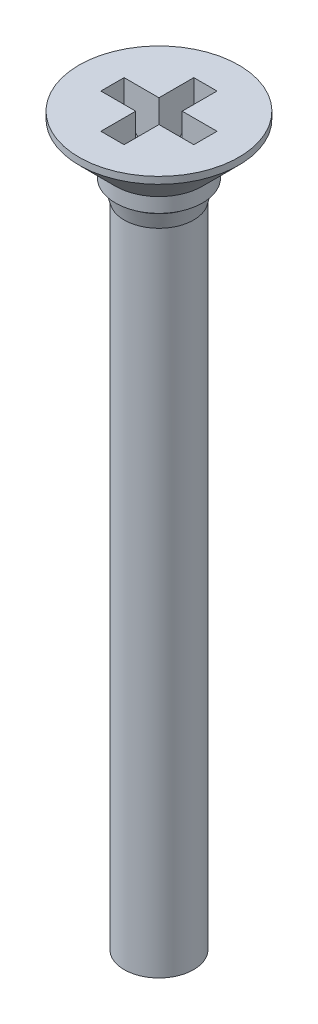
SolidWorks part; units mm, degrees
ref_plane "Vorderseite" through (0, 0, 0) normal (0, 0, 1) x (1, 0, 0)
ref_plane "Oben" through (0, 0, 0) normal (0, 1, 0) x (1, 0, 0)
ref_plane "Rechts" through (0, 0, 0) normal (1, 0, 0) x (0, 0, -1)
sketch "Skizze1" plane through (0, 0, 0) normal (0, 0, 1) x (1, 0, 0)
  line L0 (0, 0) -> (2.75, 0)
  line L1 (2.75, 0) -> (2.75, -0.2375)
  line L2 (2.75, -0.2375) -> (1.5, -1.4875)
  line L3 (1.3375, -1.9875) -> (1.3375, -2.1126)
  line L4 (1.3375, -2.1126) -> (1.1935, -2.65)
  line L5 (1.1935, -2.65) -> (1.1935, -8)
  line L6 (1.1935, -8) -> (0, -8)
  line L7 (0, 0) -> (0, -8) construction
  line L8 (0, 0) -> (0, -8)
  line L10 (1.5, -1.4875) -> (1.5, -1.9875)
  line L12 (1.5, -1.9875) -> (1.3375, -1.9875)
  point P3 (1.3375, -1.65)
  dimension "D1" = 45
  dimension "D2" = 15
  dimension "K" = 1.65
  dimension "DA" = 5.5
  dimension "DK" = 2.387
  dimension "L" = 8
  dimension "DG" = 3
  dimension "A" = 1
  dimension "DF" = 2.675
  dimension "P" = 0.5
revolve "Basis-Rotation" add sketch "Skizze1" angle 360 about L7
sketch "Skizze2" plane through (0, 0, 0) normal (0, 0, 1) x (1, 0, 0)
  line L0 (0, -2.1) -> (0, 0) construction
  line L1 (0, 0) -> (0, -8) construction
  line L2 (-0.55, -2.1) -> (0.55, -2.1)
  line L3 (1.6, 0) -> (1.6, -1.05)
  line L4 (1.6, -1.05) -> (0.55, -2.1)
  line L5 (1.6, 0) -> (-1.6, 0)
  line L6 (-1.6, -1.05) -> (-0.55, -2.1)
  line L7 (-1.6, 0) -> (-1.6, -1.05)
  line L8 (0, -1.05) -> (1.6, -1.05) construction
  line L9 (2.75, 0) -> (-2.75, 0) construction
  line L11 (1.5, -1.4875) -> (2.75, -0.2375) construction
  point P11 (0, 0)
  dimension "M" = 3.2
  dimension "T" = 2.1
extrude "Kreuzschlitz1 H" cut sketch "Skizze2" against normal blind 0.4 and the other way blind 0.4
sketch "Skizze3" plane through (0, 0, 0) normal (1, 0, 0) x (0, 0, -1)
  line L0 (0, -2.1) -> (0, 0) construction
  line L2 (-0.55, -2.1) -> (0.55, -2.1)
  line L3 (1.6, 0) -> (1.6, -1.05)
  line L4 (1.6, -1.05) -> (0.55, -2.1)
  line L5 (1.6, 0) -> (-1.6, 0)
  line L6 (-1.6, -1.05) -> (-0.55, -2.1)
  line L7 (-1.6, 0) -> (-1.6, -1.05)
  line L8 (0, -1.05) -> (1.6, -1.05) construction
  point P11 (0, 0)
extrude "Kreuzschlitz2 H" cut sketch "Skizze3" against normal blind 0.4 and the other way blind 0.4
sketch "Skizze4" plane through (2.4522, 0, -1.8507) normal (0, 1, 0) x (-1, 0, 0)
  line L0 (7.3522, 1.8507) -> (-2.4478, 1.8507) construction
  line L1 (2.4522, -3.0493) -> (2.4522, 6.7507) construction
  line L2 (-2.4478, 1.0342) -> (-2.4478, 2.6672)
  line L3 (-2.4478, 1.0342) -> (0.0059, 1.0342)
  line L4 (0.0059, 1.0342) -> (0.8191, 0.6258)
  line L5 (1.2273, 0.2176) -> (-1.0126, -1.6141)
  line L6 (0.8191, 0.6258) -> (-1.0126, -1.6141)
  line L7 (1.6357, -0.5956) -> (1.2273, 0.2176)
  line L8 (1.6357, -3.0493) -> (1.6357, -0.5956)
  line L9 (1.6357, -3.0493) -> (3.2687, -3.0493)
  line L10 (3.2687, -3.0493) -> (3.2687, -0.5956)
  line L11 (3.2687, -0.5956) -> (3.6772, 0.2176)
  line L12 (2.4522, 1.8507) -> (-1.0126, -1.6141) construction
  line L13 (4.0854, 0.6258) -> (5.917, -1.6141)
  line L14 (3.6772, 0.2176) -> (5.917, -1.6141)
  line L15 (4.8986, 1.0342) -> (4.0854, 0.6258)
  line L16 (7.3522, 1.0342) -> (4.8986, 1.0342)
  line L17 (7.3522, 1.0342) -> (7.3522, 2.6672)
  line L18 (7.3522, 2.6672) -> (4.8986, 2.6672)
  line L19 (4.8986, 2.6672) -> (4.0854, 3.0757)
  line L20 (3.6772, 3.4839) -> (5.917, 5.3156)
  line L21 (4.0854, 3.0757) -> (5.917, 5.3156)
  line L22 (3.2687, 4.2971) -> (3.6772, 3.4839)
  line L23 (3.2687, 6.7507) -> (3.2687, 4.2971)
  line L24 (1.6357, 6.7507) -> (3.2687, 6.7507)
  line L25 (1.6357, 6.7507) -> (1.6357, 4.2971)
  line L26 (1.6357, 4.2971) -> (1.2273, 3.4839)
  line L27 (0.8191, 3.0757) -> (-1.0126, 5.3156)
  line L28 (1.2273, 3.4839) -> (-1.0126, 5.3156)
  line L29 (0.0059, 2.6672) -> (0.8191, 3.0757)
  line L30 (-2.4478, 2.6672) -> (0.0059, 2.6672)
  circle A0 centre (2.4522, 1.8507) radius 4.9 construction
  circle A1 centre (2.4522, 1.8507) radius 2.0415 construction
  circle A2 centre (2.4522, 1.8507) radius 2.579 construction
  dimension "X2" = 4.083
  dimension "X1" = 5.158
  dimension "M" = 9.8
  dimension "D3" = 5.725
  dimension "X3" = 1.633
sketch "Sketch1" plane through (0, -8, 0) normal (0, -1, 0) x (1, 0, 0)
  circle A0 centre (0, 0) radius 1.1935
extrude "Boss-Extrude1" add sketch "Sketch1" along normal blind 17
